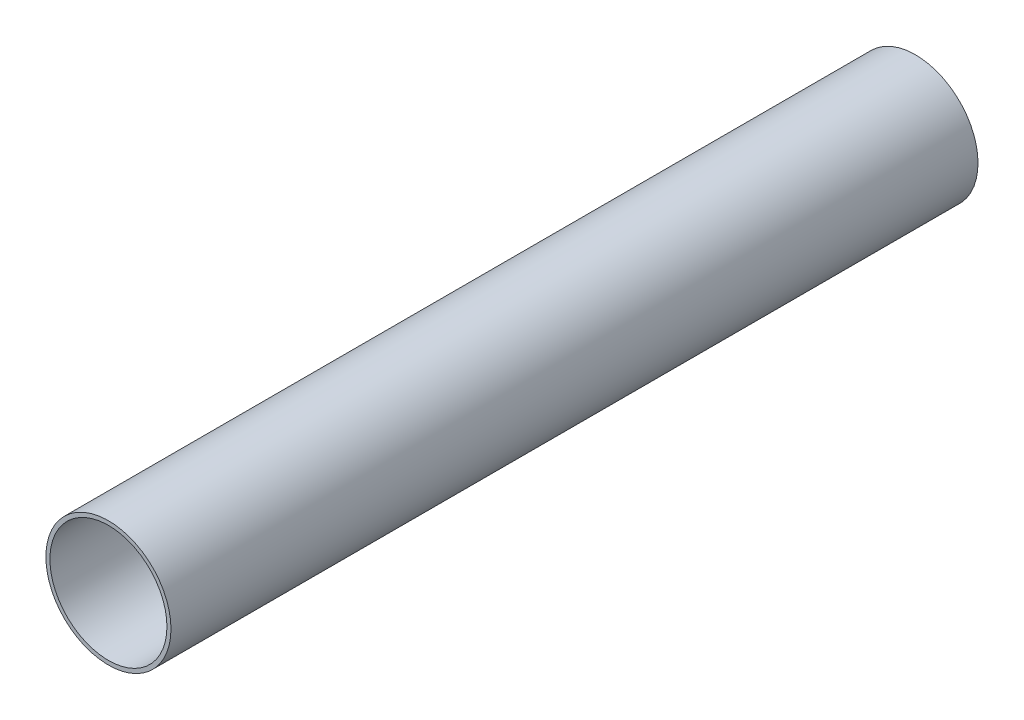
SolidWorks part; units mm, degrees
ref_plane "Front Plane" through (0, 0, 0) normal (0, 0, 1) x (1, 0, 0)
ref_plane "Top Plane" through (0, 0, 0) normal (0, 1, 0) x (1, 0, 0)
ref_plane "Right Plane" through (0, 0, 0) normal (1, 0, 0) x (0, 0, -1)
sketch "Sketch1" plane through (0, 0, 0) normal (0, 0, 1) x (1, 0, 0)
  circle A4 centre (-9.3291, 10.4952) radius 15.5
  circle A5 centre (-9.3291, 10.4952) radius 14.5
  dimension "D1" = 31
  dimension "D2" = 29
extrude "Boss-Extrude2" add sketch "Sketch1" along normal blind 200
